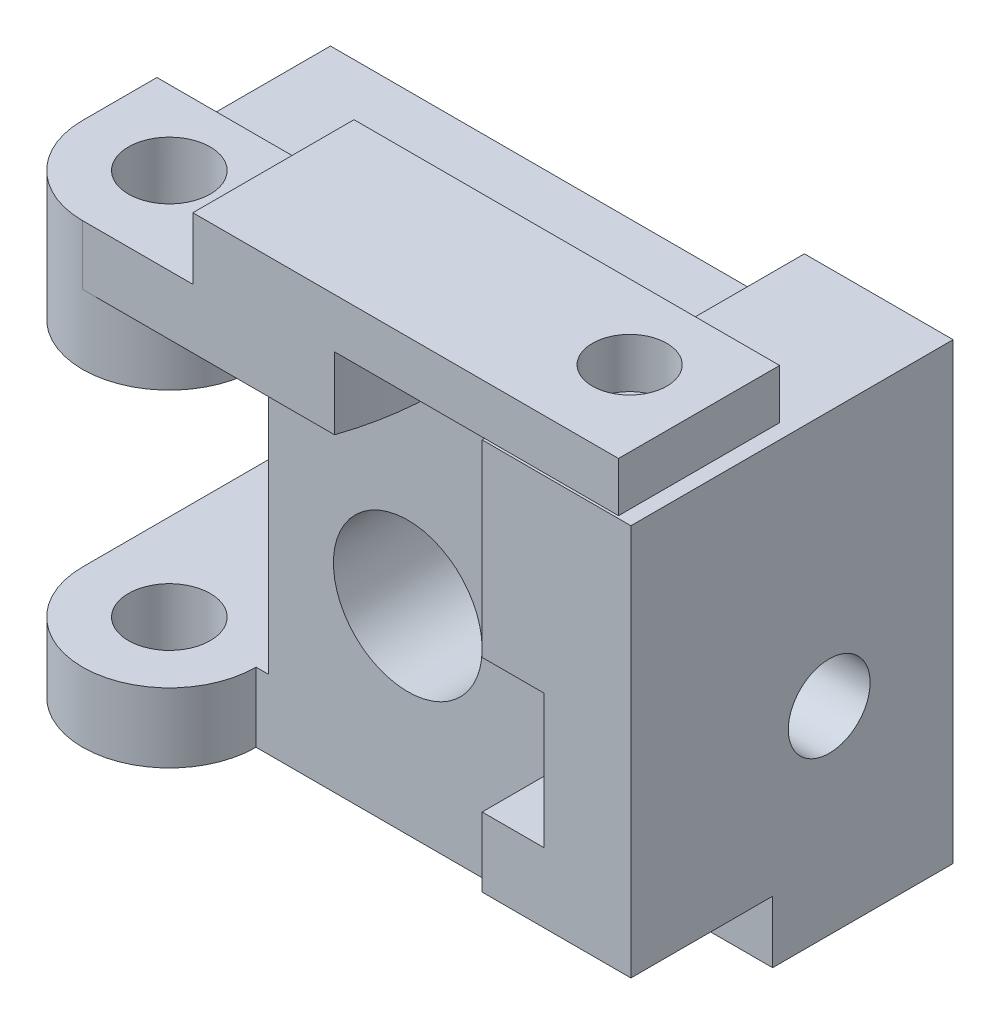
SolidWorks part; units mm, degrees
ref_plane "Płaszczyzna przednia" through (0, 0, 0) normal (0, 0, 1) x (1, 0, 0)
ref_plane "Płaszczyzna górna" through (0, 0, 0) normal (0, 1, 0) x (1, 0, 0)
ref_plane "Płaszczyzna prawa" through (0, 0, 0) normal (1, 0, 0) x (0, 0, -1)
sketch "Szkic2" plane through (0, 0, 0) normal (0, 0, 1) x (1, 0, 0)
  line L1 (-5.6197, 8) -> (12, 8)
  line L2 (-5.6197, 8) -> (-5.6197, -8)
  line L3 (-5.6197, -8) -> (12, -8)
  line L4 (12, 8) -> (12, -8)
  circle A0 centre (0, 0) radius 3
  dimension "D1" = 6
  dimension "D2" = 8
  dimension "D3" = 8
  dimension "D4" = 12
extrude "Dodanie-wyciągnięcie1" add sketch "Szkic2" along normal blind 10
sketch "Szkic3" plane through (12, 0, 0) normal (1, 0, 0) x (0, 0, -1)
  line L0 (-10, -8) -> (-10, 8) construction
  circle A0 centre (-5, 0) radius 1.65
  dimension "D2" = 3.3
  dimension "D1" = 5
extrude "Wytnij-wyciągnięcie1" cut sketch "Szkic3" against normal blind 10
ref_plane "Płaszczyzna4" through (6, 0, 0) normal (1, 0, 0) x (0, 0, -1)
sketch "Szkic5" plane through (6, 0, 0) normal (1, 0, 0) x (0, 0, -1)
  line L0 (-8.4185, 3.25) -> (-10, 3.25)
  line L1 (-8.4185, 3.25) -> (-1.5815, 3.25)
  line L3 (-8.4185, -3.25) -> (-1.5815, -3.25)
  line L4 (-1.5815, 3.25) -> (-1.5815, -3.25)
  line L5 (-8.4185, 3.25) -> (-1.5815, -3.25) construction
  line L6 (-8.4185, -3.25) -> (-1.5815, 3.25) construction
  line L7 (-10, -8) -> (-10, 8) construction
  line L8 (-10, 3.25) -> (-10, -3.25)
  line L9 (-10, -3.25) -> (-8.4185, -3.25)
  point P0 (-5, 0)
  dimension "D1" = 6.5
extrude "Wytnij-wyciągnięcie2" cut sketch "Szkic5" along normal blind 2.5
sketch "Szkic6" plane through (6, 0, 0) normal (1, 0, 0) x (0, 0, -1)
  line L0 (-3.2102, 3.1) -> (-3.2102, 3.2563)
  line L6 (-1.5911, 0.2956) -> (-3.2102, 3.1)
  line L7 (-3.2102, 3.2563) -> (-1.5911, 3.2563)
  line L8 (-1.5911, 3.2563) -> (-1.5911, 0.2956)
  line L9 (-1.5911, 0.2956) -> (-3.2102, 3.1)
extrude "Dodanie-wyciągnięcie2" add sketch "Szkic6" along normal blind 2.5 contours L8 L7 L0 L6
mirror "Lustro1" about plane through (0, 0, 0) normal (0, 1, 0) of "Dodanie-wyciągnięcie2"
sketch "Szkic7" plane through (0, -8, 0) normal (0, -1, 0) x (1, 0, 0)
  line L0 (-5.6197, 10) -> (-11.9129, 10) construction
  line L1 (-5.6197, 10) -> (-5.6197, 0) construction
  line L2 (-13.1197, 10) -> (-13.1197, 0)
  line L3 (-13.1197, 0) -> (-5.6197, 0)
  line L4 (-5.6197, 0) -> (-5.6197, 10)
  line L5 (-5.6197, 10) -> (-6.1197, 10)
  circle A0 centre (-9.6197, 10) radius 1.65
  arc A1 (-6.1197, 10) -> (-13.1197, 10) centre (-9.6197, 10) ccw
  dimension "D1" = 3.3
  dimension "D3" = 7
  dimension "D2" = 4
extrude "Dodanie-wyciągnięcie4" add sketch "Szkic7" against normal blind 2.8
mirror "Lustro2" about plane through (0, 0, 0) normal (0, 1, 0) of "Dodanie-wyciągnięcie4"
sketch "Szkic10" plane through (0, 8, 0) normal (0, 1, 0) x (1, 0, 0)
  line L0 (-6.1197, -13.5) -> (0.5445, -13.5)
  line L3 (-6.1197, -7) -> (0.7032, -7)
  line L5 (-13.1197, -7) -> (-13.1197, -10) construction
  line L6 (-13.1197, -10) -> (-13.1197, 0) construction
  line L9 (-6.1197, -7) -> (-13.1197, -7)
  line L11 (-6.1197, -13.5) -> (-9.6197, -13.5)
  line L12 (-13.1197, -7) -> (-13.1197, -10)
  line L13 (-13.1197, -13.5) -> (-13.1197, -15.5772) construction
  arc A0 (0.5445, -13.5) -> (0.7032, -7) centre (-9.6197, -10) ccw
  arc A2 (-13.1197, -10) -> (-9.6197, -13.5) centre (-9.6197, -10) ccw
  circle A3 centre (-9.6197, -10) radius 1.65
  dimension "D1" = 21.5
extrude "Dodanie-wyciągnięcie5" add sketch "Szkic10" along normal blind 2.9
sketch "Szkic11" plane through (0, 10.9, 0) normal (0, 1, 0) x (1, 0, 0)
  line L0 (12, -13.5) -> (12, -14.824) construction
  line L1 (12, -13.5) -> (14.0211, -13.5) construction
  line L2 (-13.1197, -7) -> (-13.1197, -10) construction
  line L7 (12, -10) -> (12, 0) construction
  line L8 (12, -7) -> (-13.1197, -7)
  line L9 (12, -7) -> (12, -13.5)
  line L10 (12, -13.5) -> (-9.6197, -13.5)
  line L11 (-13.1197, -7) -> (-13.1197, -10)
  line L12 (-13.1197, -13.5) -> (-13.1197, -16.2399) construction
  circle A0 centre (-9.6197, -10) radius 1.65
  arc A2 (-13.1197, -10) -> (-9.6197, -13.5) centre (-9.6197, -10) ccw
  arc A3 (-13.1197, -10) -> (-9.6197, -13.5) centre (-9.6197, -10) ccw
  dimension "D1" = 0
extrude "Dodanie-wyciągnięcie6" add sketch "Szkic11" along normal blind 2
sketch "Szkic12" plane through (0, 8, 0) normal (0, 1, 0) x (1, 0, 0)
  line L0 (6, -7.425) -> (6, 7.425) construction
  line L1 (12, 0) -> (6, 0)
  line L2 (12, 0) -> (12, -13)
  line L3 (12, -13) -> (6, -13)
  line L4 (6, 0) -> (6, -13)
  line L5 (12, -10) -> (1.1303, -10) construction
  dimension "D1" = 3
extrude "Dodanie-wyciągnięcie7" add sketch "Szkic12" along normal blind 2.3
sketch "Szkic16" plane through (0, 8, 0) normal (0, -1, 0) x (1, 0, 0)
  line L0 (6, -7.425) -> (6, 7.425) construction
  line L1 (12, 13) -> (6, 13)
  line L2 (12, 13) -> (12, 10)
  line L3 (12, 10) -> (6, 10)
  line L4 (6, 13) -> (6, 10)
  line L5 (-6.1197, 10) -> (12, 10) construction
extrude "Dodanie-wyciągnięcie12" add sketch "Szkic16" along normal up to surface (4.75 mm away) up to face at (7.25, 3.25, 6.6051)
sketch "Szkic17" plane through (0, 3.25, 0) normal (0, -1, 0) x (1, 0, 0)
  line L1 (12, 13) -> (8.5, 13)
  line L2 (12, 13) -> (12, 10)
  line L3 (12, 10) -> (8.5, 10)
  line L4 (8.5, 13) -> (8.5, 10)
extrude "Dodanie-wyciągnięcie13" add sketch "Szkic17" along normal up to surface (6.5 mm away) up to face at (7.25, -3.25, 6.6051)
sketch "Szkic18" plane through (0, -3.25, 0) normal (0, -1, 0) x (1, 0, 0)
  line L0 (6, -7.425) -> (6, 7.425) construction
  line L1 (12, 13) -> (6, 13)
  line L2 (12, 13) -> (12, 9.6457)
  line L3 (12, 9.6457) -> (6, 9.6457)
  line L4 (6, 13) -> (6, 9.6457)
extrude "Dodanie-wyciągnięcie14" add sketch "Szkic18" along normal up to surface (4.75 mm away) up to face at (-1.6718, -8, 6.7)
sketch "Szkic19" plane through (0, 12.9, 0) normal (0, 1, 0) x (1, 0, 0)
  line L1 (12, -13) -> (12, 0) construction
  circle A0 centre (9, -10) radius 1.1812
  dimension "D1" = 3
  dimension "D2" = 3
extrude "Wytnij-wyciągnięcie3" cut sketch "Szkic19" against normal up to surface (20.9 mm away) up to face at (0.5201, -8, 8.5)
sketch "Szkic21" plane through (0, 0, 1.5815) normal (0, 0, 1) x (1, 0, 0)
  line L0 (6, -7.425) -> (6, 7.425) construction
  line L1 (6, 3.2566) -> (8.5, 3.2566)
  line L2 (6, 3.2566) -> (6, 2.7)
  line L3 (6, 2.7) -> (8.5, 2.7)
  line L4 (8.5, 3.2566) -> (8.5, 2.7)
  line L5 (8.5, -3.25) -> (8.5, 3.25) construction
  line L6 (8.5, 0) -> (5.5718, 0) construction
  line L7 (8.5, -3.25) -> (8.5, 3.25) construction
  dimension "D1" = 2.7
extrude "Dodanie-wyciągnięcie15" add sketch "Szkic21" along normal up to surface (11.4185 mm away)
mirror "Lustro3" about plane through (0, 0, 0) normal (0, 1, 0) of "Dodanie-wyciągnięcie15"
sketch "Szkic22" plane through (0, -8, 0) normal (0, -1, 0) x (1, 0, 0)
  circle A0 centre (9, 10) radius 1.1812
extrude "Wytnij-wyciągnięcie4" cut sketch "Szkic22" against normal up to surface (18.3 mm away) up to face at (9, 10.3, 8.8188)
sketch "Szkic34" plane through (0, 12.9, 0) normal (0, 1, 0) x (1, 0, 0)
  line L1 (-13.1197, -7) -> (-5.1704, -7)
  line L2 (-13.1197, -7) -> (-13.1197, -13.5)
  line L3 (-13.1197, -13.5) -> (-5.1704, -13.5)
  line L4 (-5.1704, -7) -> (-5.1704, -13.5)
extrude "Wytnij-wyciągnięcie5" cut sketch "Szkic34" against normal blind 2.5
sketch "Szkic35" plane through (0, -8, 0) normal (0, -1, 0) x (1, 0, 0)
  line L1 (12, 13) -> (5.36, 13)
  line L2 (12, 13) -> (12, 7.283)
  line L3 (12, 7.283) -> (5.36, 7.283)
  line L4 (5.36, 13) -> (5.36, 7.283)
extrude "Wytnij-wyciągnięcie6" cut sketch "Szkic35" against normal blind 2.5
ref_plane "Płaszczyzna5" through (0, 15, 0) normal (0, 1, 0) x (1, 0, 0)
sketch "Szkic36" plane through (0, 15, 0) normal (0, 1, 0) x (1, 0, 0)
  circle A0 centre (8.9497, -10.0003) radius 1.5
  dimension "D1" = 3
extrude "Wytnij-wyciągnięcie7" cut sketch "Szkic36" against normal blind 21
